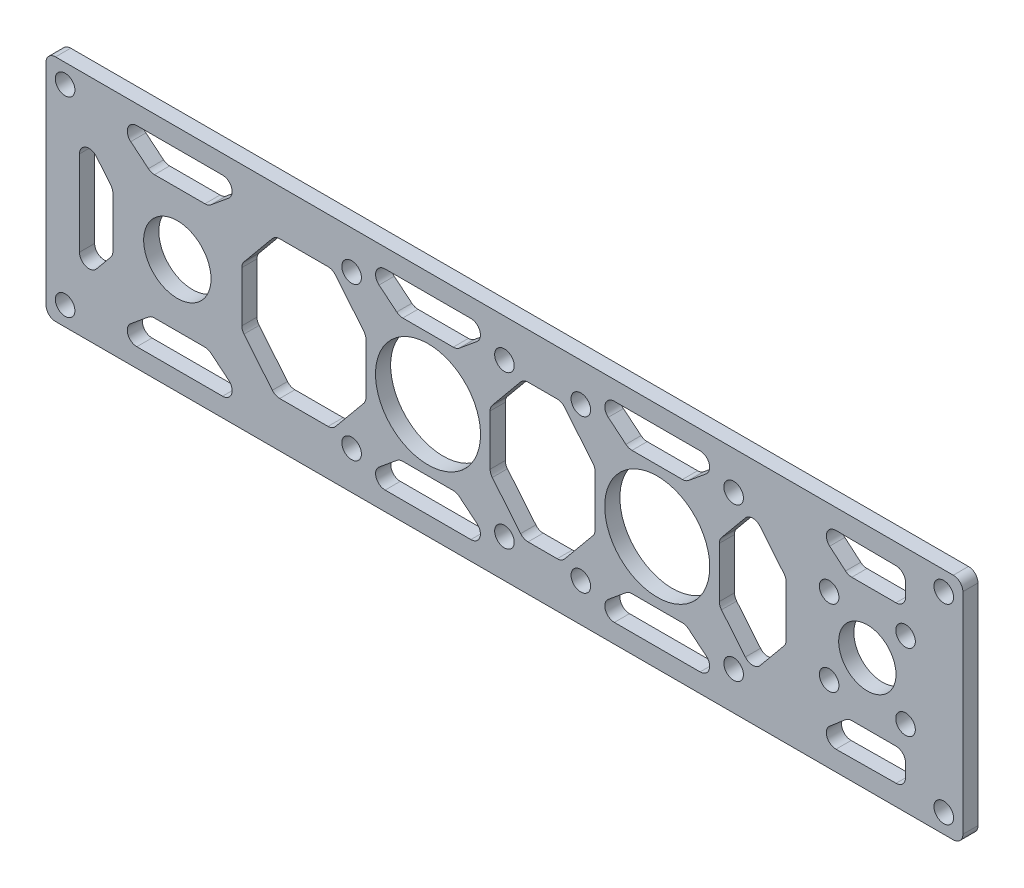
SolidWorks part; units mm, degrees
ref_plane "Front Plane" through (0, 0, 0) normal (0, 0, 1) x (1, 0, 0)
ref_plane "Top Plane" through (0, 0, 0) normal (0, 1, 0) x (1, 0, 0)
ref_plane "Right Plane" through (0, 0, 0) normal (1, 0, 0) x (0, 0, -1)
sketch "Sketch1" plane through (0, 0, 0) normal (0, 0, 1) x (1, 0, 0)
  line L0 (0, 0) -> (50000, 0) construction
  line L1 (48, -24) -> (-48, -24)
  line L2 (48, 0) -> (48, 24)
  line L3 (48, 24) -> (-48, 24)
  line L5 (48, -24) -> (-48, 24) construction
  line L6 (48, 24) -> (-48, -24) construction
  line L7 (0, 0) -> (0, -50000) construction
  line L8 (-38.5449, 20.05) -> (-30, 13)
  line L9 (-40, 16) -> (-8, 16) construction
  line L10 (-40, 16) -> (-40, -16) construction
  line L11 (-40, -16) -> (-8, -16) construction
  line L12 (-8, 16) -> (-8, -16) construction
  line L13 (-40, 16) -> (-8, -16) construction
  line L14 (-40, -16) -> (-8, 16) construction
  line L15 (-30, 13) -> (-18, 13)
  line L16 (-18, 13) -> (-9.4551, 20.05)
  line L17 (-9.4551, 20.05) -> (-38.5449, 20.05)
  line L18 (50, 26) -> (-50, 26) construction
  line L19 (-50, -26) -> (-50, 26) construction
  line L20 (50, -26) -> (-50, -26) construction
  line L21 (50, -26) -> (50, 26) construction
  line L22 (44, 20) -> (-44, 20) construction
  line L23 (-44, -20) -> (-44, -14.4843) construction
  line L24 (44, -20) -> (-44, -20) construction
  line L25 (44, -20) -> (44, -14.4843) construction
  line L26 (-18, -13) -> (-9.4551, -20.05)
  line L27 (-30, -13) -> (-18, -13)
  line L28 (-38.5449, -20.05) -> (-30, -13)
  line L29 (-9.4551, -20.05) -> (-38.5449, -20.05)
  line L31 (-44, -14.4843) -> (-37, -6) construction
  line L32 (-37, -6) -> (-37, 6) construction
  line L33 (-37, 6) -> (-44, 14.4843) construction
  line L34 (-24, 0) -> (-24, 50000) construction
  line L35 (-11, -6) -> (-11, 6)
  line L36 (-4, -14.4843) -> (-11, -6)
  line L38 (-11, 6) -> (-4, 14.4843)
  line L39 (4, -14.4843) -> (11, -6)
  line L41 (11, 6) -> (4, 14.4843)
  line L42 (11, -6) -> (11, 6)
  line L43 (30, -13) -> (18, -13)
  line L44 (38.5449, -20.05) -> (30, -13)
  line L45 (9.4551, -20.05) -> (38.5449, -20.05)
  line L46 (18, -13) -> (9.4551, -20.05)
  line L47 (37, -6) -> (37, 6)
  line L48 (44, -14.4843) -> (37, -6)
  line L50 (37, 6) -> (44, 14.4843)
  line L51 (18, 13) -> (9.4551, 20.05)
  line L52 (30, 13) -> (18, 13)
  line L53 (38.5449, 20.05) -> (30, 13)
  line L54 (9.4551, 20.05) -> (38.5449, 20.05)
  line L55 (-44, -14.4843) -> (-37, -6)
  line L57 (-37, 6) -> (-44, 14.4843)
  line L58 (-37, -6) -> (-37, 6)
  line L59 (-4, 14.4843) -> (4, 14.4843)
  line L60 (-4, -14.4843) -> (4, -14.4843)
  line L61 (48, -24) -> (48, 24) construction
  line L62 (48, 24) -> (88, 24)
  line L63 (48, 24) -> (48, 0)
  line L64 (48, -24) -> (88, -24)
  line L65 (88, 24) -> (88, -24)
  line L66 (76, -8) -> (60, -8) construction
  line L67 (76, -8) -> (76, 8) construction
  line L68 (76, 8) -> (60, 8) construction
  line L69 (60, -8) -> (60, 8) construction
  line L70 (76, -8) -> (60, 8) construction
  line L71 (76, 8) -> (60, -8) construction
  line L80 (-48, 24) -> (-104, 24)
  line L81 (-104, 24) -> (-104, -24)
  line L82 (-104, -24) -> (-48, -24)
  line L83 (-76.4956, 19.1) -> (-24, 19.1)
  line L84 (-76.4956, -19.1) -> (-24, -19.1)
  line L85 (-70, -13) -> (-82, -13)
  line L86 (-48, -24) -> (-48, 24) construction
  line L87 (-61.4551, -20.05) -> (-70, -13)
  line L88 (-90.5449, -20.05) -> (-61.4551, -20.05)
  line L89 (-82, -13) -> (-90.5449, -20.05)
  line L90 (-82, 13) -> (-90.5449, 20.05)
  line L91 (-70, 13) -> (-82, 13)
  line L92 (-61.4551, 20.05) -> (-70, 13)
  line L93 (-90.5449, 20.05) -> (-61.4551, 20.05)
  line L95 (-63, 6) -> (-56, 14.4843)
  line L96 (-63, -6) -> (-63, 6)
  line L97 (-56, -14.4843) -> (-63, -6)
  line L98 (-56, 14.4843) -> (-44, 14.4843)
  line L99 (-56, -14.4843) -> (-44, -14.4843)
  line L100 (-44, 14.4843) -> (-44, 20) construction
  line L101 (-44, -20) -> (-44, 20) construction
  line L102 (-76.4956, 0) -> (-76.4956, -50000) construction
  line L103 (-89.9912, 6) -> (-96.9912, 14.4843)
  line L104 (-89.9912, -6) -> (-89.9912, 6)
  line L105 (-96.9912, -14.4843) -> (-89.9912, -6)
  line L106 (-96.9912, 14.4843) -> (-96.9912, -14.4843)
  line L107 (44, -14.4843) -> (51, -6)
  line L108 (88, 24) -> (84, 24) construction
  line L109 (88, 24) -> (88, 20) construction
  line L110 (88, 20) -> (84, 20) construction
  line L111 (84, 24) -> (84, 20) construction
  line L112 (-104, -24) -> (-100, -24) construction
  line L113 (-104, -24) -> (-104, -20) construction
  line L114 (-104, -20) -> (-100, -20) construction
  line L115 (-100, -24) -> (-100, -20) construction
  line L116 (51, 6) -> (44, 14.4843)
  line L117 (51, -6) -> (51, 6)
  line L118 (44, 14.4843) -> (44, 20) construction
  line L119 (44, -20) -> (44, 20) construction
  line L120 (44, 0) -> (44, -50000) construction
  line L121 (64, -13) -> (76, -13)
  line L122 (76, -13) -> (76, -19.7067)
  line L124 (55.9393, -19.8906) -> (64, -13)
  line L125 (76, 8) -> (76, -19.7067) construction
  line L126 (38.5449, -20.05) -> (50036.4448, 438.22) construction
  line L127 (76, -24) -> (76, -49992) construction
  line L128 (55.9393, -19.8906) -> (76, -19.7067)
  line L129 (55.9393, 19.8906) -> (64, 13)
  line L130 (64, 13) -> (76, 13)
  line L131 (76, 13) -> (76, 19.7067)
  line L132 (55.9393, 19.8906) -> (76, 19.7067)
  circle A0 centre (-40, 16) radius 2.05
  circle A1 centre (-8, 16) radius 2.05
  circle A2 centre (-8, -16) radius 2.05
  circle A3 centre (-40, -16) radius 2.05
  circle A4 centre (-24, 0) radius 11
  circle A5 centre (-8, -16) radius 4.05 construction
  circle A6 centre (-40, -16) radius 4.05 construction
  circle A7 centre (-24, 0) radius 13 construction
  circle A8 centre (-40, 16) radius 4.05 construction
  circle A9 centre (-8, 16) radius 4.05 construction
  circle A10 centre (-8, -16) radius 0.05 construction
  circle A11 centre (-40, -16) radius 0.05 construction
  circle A12 centre (-24, 0) radius 9 construction
  circle A13 centre (-40, 16) radius 0.05 construction
  circle A14 centre (-8, 16) radius 0.05 construction
  circle A15 centre (8, 16) radius 2.05
  circle A16 centre (8, -16) radius 2.05
  circle A17 centre (40, -16) radius 2.05
  circle A18 centre (24, 0) radius 11
  circle A19 centre (40, 16) radius 2.05
  circle A20 centre (-36.7, 0) radius 2.05 construction
  circle A21 centre (11.3, 0) radius 2.05 construction
  circle A22 centre (68, 0) radius 6
  circle A23 centre (76, 8) radius 2.05
  circle A24 centre (76, -8) radius 2.05
  circle A25 centre (60, -8) radius 2.05
  circle A26 centre (60, 8) radius 2.05
  circle A27 centre (-24, 0) radius 19.1 construction
  circle A28 centre (-76.4956, 0) radius 19.1 construction
  arc A29 (-24, 19.1) -> (-24, -19.1) centre (-24, 0) cw
  arc A30 (-76.4956, 19.1) -> (-76.4956, -19.1) centre (-76.4956, 0) ccw
  circle A31 centre (-76.4956, 0) radius 7.05
  circle A32 centre (84, 20) radius 2.05
  circle A33 centre (84, -20) radius 2.05
  circle A34 centre (-100, -20) radius 2.05
  circle A35 centre (-100, 20) radius 2.05
  point P0 (0, 0)
  point P10 (-24, 0)
  point P100 (68, 0)
  dimension "D5" = 4.1
  dimension "D6" = 22
  dimension "D18" = 4.1
  dimension "D19" = 12
  dimension "D22" = 38.2
  dimension "D24" = 225
  dimension "D14" = 14.1
  dimension "D27" = 4.1
  dimension "D1" = 96
  dimension "D2" = 48
  dimension "D3" = 32
  dimension "D4" = 27.5044
  dimension "D11" = 12
  dimension "D12" = 12
  dimension "D13" = 48
  dimension "D15" = 40
  dimension "D16" = 16
  dimension "D17" = 12
  dimension "D20" = 44
  dimension "D21" = 40
  dimension "D23" = 192
  dimension "D25" = 4
  dimension "D26" = 4
  dimension "D28" = 4
  dimension "D29" = 4
  dimension "D7" = 2
  dimension "D8" = 2
  dimension "D9" = 2
  dimension "D10" = 4
extrude "Boss-Extrude1" add sketch "Sketch1" along normal blind 3.175
fillet "Fillet1" radius 2 62 edges at (-104, 24, 1.5875) (-104, -24, 1.5875) (88, 24, 1.5875) (88, -24, 1.5875) (55.9393, -19.8906, 1.5875) (76, -19.7067, 1.5875) (76, -13, 1.5875) (64, -13, 1.5875) (64, 13, 1.5875) (76, 13, 1.5875) (55.9393, 19.8906, 1.5875) (76, 19.7067, 1.5875) (44, 14.4843, 1.5875) (51, 6, 1.5875) (44, -14.4843, 1.5875) (51, -6, 1.5875) (37, -6, 1.5875) (37, 6, 1.5875) (9.4551, -20.05, 1.5875) (38.5449, -20.05, 1.5875) (18, -13, 1.5875) (30, -13, 1.5875) (38.5449, 20.05, 1.5875) (9.4551, 20.05, 1.5875) (18, 13, 1.5875) (30, 13, 1.5875) (11, -6, 1.5875) (11, 6, 1.5875) (-11, -6, 1.5875) (-11, 6, 1.5875) (-4, -14.4843, 1.5875) (4, -14.4843, 1.5875) (4, 14.4843, 1.5875) (-4, 14.4843, 1.5875) (-9.4551, 20.05, 1.5875) (-38.5449, 20.05, 1.5875) (-30, 13, 1.5875) (-18, 13, 1.5875) (-9.4551, -20.05, 1.5875) (-38.5449, -20.05, 1.5875) (-30, -13, 1.5875) (-18, -13, 1.5875) (-37, 6, 1.5875) (-44, 14.4843, 1.5875) (-56, -14.4843, 1.5875) (-44, -14.4843, 1.5875) (-37, -6, 1.5875) (-56, 14.4843, 1.5875) (-63, -6, 1.5875) (-63, 6, 1.5875) (-90.5449, 20.05, 1.5875) (-61.4551, 20.05, 1.5875) (-82, 13, 1.5875) (-70, 13, 1.5875) (-90.5449, -20.05, 1.5875) (-61.4551, -20.05, 1.5875) (-70, -13, 1.5875) (-82, -13, 1.5875) (-96.9912, 14.4843, 1.5875) (-89.9912, 6, 1.5875) (-89.9912, -6, 1.5875) (-96.9912, -14.4843, 1.5875)
